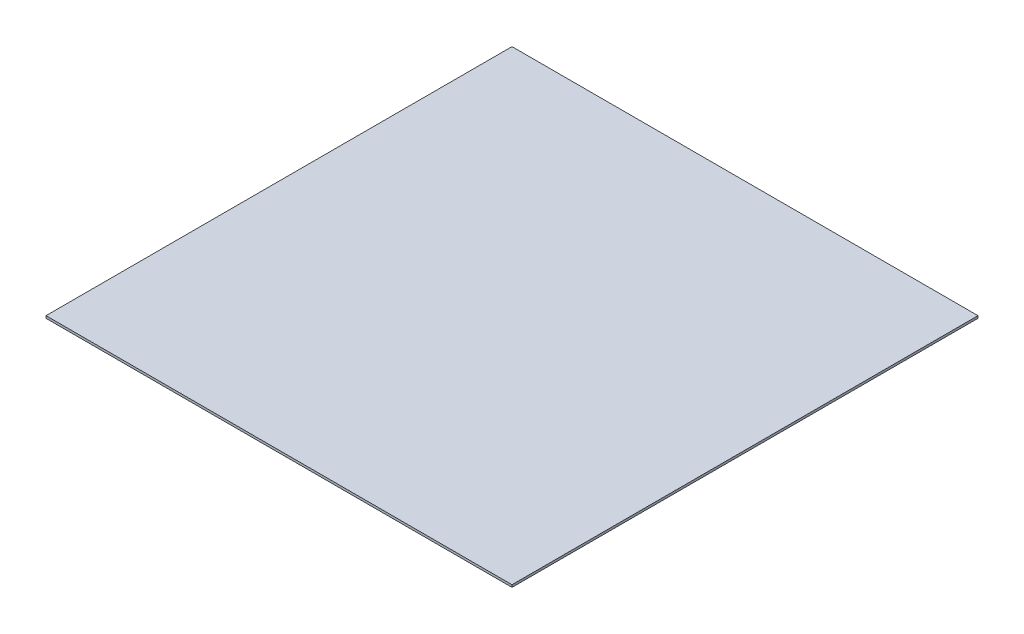
SolidWorks part; units mm, degrees
ref_plane "Front Plane" through (0, 0, 0) normal (0, 0, 1) x (1, 0, 0)
ref_plane "Top Plane" through (0, 0, 0) normal (0, 1, 0) x (1, 0, 0)
ref_plane "Right Plane" through (0, 0, 0) normal (1, 0, 0) x (0, 0, -1)
sketch "Sketch1" plane through (0, 0, 0) normal (0, 1, 0) x (1, 0, 0)
  line L1 (300, -300) -> (-300, -300)
  line L2 (300, -300) -> (300, 300)
  line L3 (300, 300) -> (-300, 300)
  line L4 (-300, -300) -> (-300, 300)
  line L5 (300, -300) -> (-300, 300) construction
  line L6 (300, 300) -> (-300, -300) construction
  point P0 (0, 0)
  dimension "D1" = 600
  dimension "D2" = 600
extrude "Boss-Extrude1" add sketch "Sketch1" along normal mid plane 3
